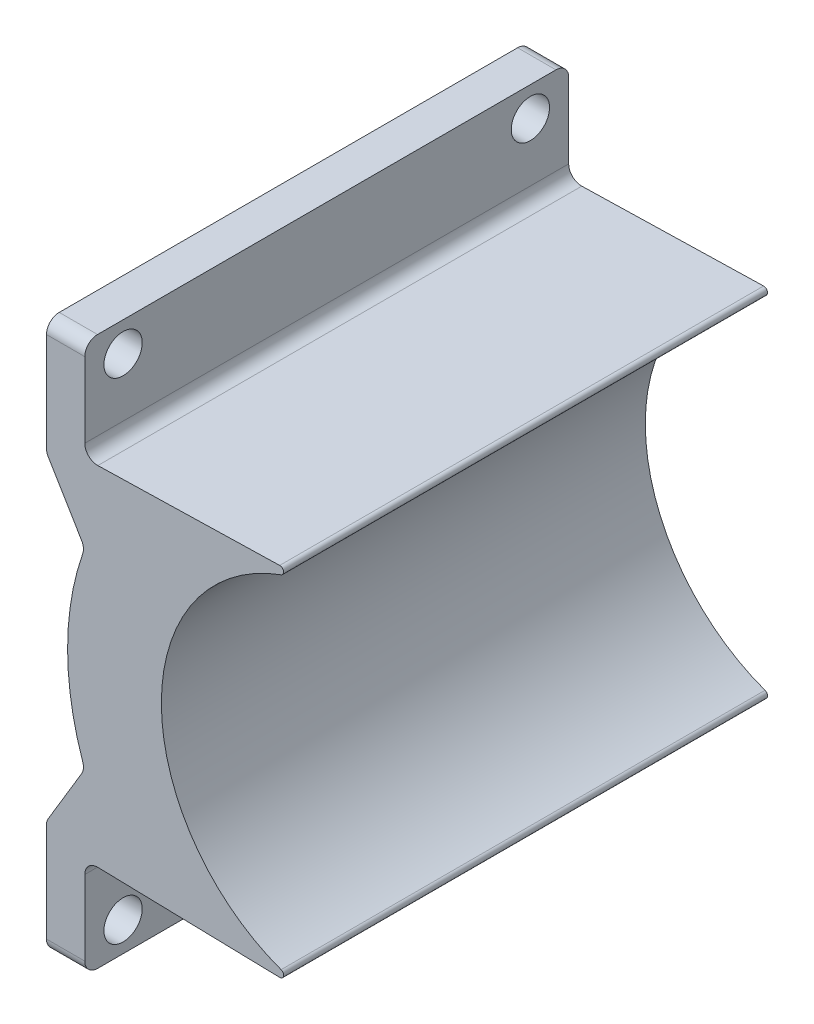
SolidWorks part; units mm, degrees
ref_plane "前视基准面" through (0, 0, 0) normal (0, 0, 1) x (1, 0, 0)
ref_plane "上视基准面" through (0, 0, 0) normal (0, 1, 0) x (1, 0, 0)
ref_plane "右视基准面" through (0, 0, 0) normal (1, 0, 0) x (0, 0, -1)
other "Configuration Table"
sketch "草图3" plane through (0, 0, 0) normal (0, 0, 1) x (1, 0, 0)
  line L0 (0, 0) -> (0, -7.2) construction
  line L1 (0, -7.2) -> (19.3716, -7.2636) construction
  line L2 (0, 0) -> (3, 0) construction
  line L3 (3, 0) -> (3, -5.5) construction
  line L4 (3, -5.5) -> (14.2314, -2.7878) construction
  line L5 (-1.5, 0) -> (-4.5, 0)
  line L6 (-4.5, 0) -> (-4.5, -9)
  line L7 (-1.5, 0) -> (-1.5, -7.9)
  line L8 (-1.5, -7.9) -> (16.2755, -7.4665)
  line L9 (-4.5, -9) -> (-1.5, -14)
  line L10 (-6.7339, -21.5) -> (12.0368, -21.5) construction
  line L11 (-4.5, -34) -> (-1.5, -29)
  line L12 (-1.5, -35.1) -> (16.2755, -35.5335)
  line L13 (-1.5, -43) -> (-1.5, -35.1)
  line L14 (-1.5, -43) -> (-4.5, -43)
  line L15 (-4.5, -43) -> (-4.5, -34)
  arc A0 (19.3716, -7.2636) -> (33, -21.5) centre (18.75, -21.5) cw construction
  arc A1 (14.2314, -2.7878) -> (38, -21.5) centre (18.75, -21.5) cw construction
  arc A2 (16.2755, -7.4665) -> (16.2755, -35.5335) centre (18.75, -21.5) ccw
  arc A3 (-1.5, -14) -> (-1.5, -29) centre (18.75, -21.5) ccw
  point P3 (12.0368, -25.9178)
  point P9 (35.0735, -25.6905)
  point P14 (-4.5536, -29.3279)
  point P21 (-1.7579, -9)
  point P22 (-4.5, -11.3653)
  point P23 (-1.8481, -15.7128)
  point P24 (-1.5, -9)
  point P25 (0, 0)
  point P26 (-1.5, -15.0914)
  point P27 (0, 0)
  point P34 (0, 0)
  point P35 (0, -7.2005)
  point P36 (0, -6.7458)
  point P37 (-13.5763, -9.2465)
  point P38 (-6.7562, -16.1113)
  point P39 (9.8393, -3.1843)
  point P40 (38, -26.2967)
  point P41 (18.1912, -8.702)
  point P42 (-4.5, -7.2)
  point P43 (-1.5, -11.141)
  point P44 (-4.5, -9.3981)
  point P45 (-1.5, -13.9448)
  point P46 (0, 0)
  point P47 (-1.5, -7.8403)
  dimension "D4" = 14.25
  dimension "D5" = 19.25
  dimension "D9" = 14.3
  dimension "D11" = 3
  dimension "D13" = 14.25
  dimension "D14" = 9
  dimension "D2" = 5.5
  dimension "D3" = 3
  dimension "D6" = 35
  dimension "D7" = 87.5
  dimension "D8" = 16
  dimension "D10" = 160
  dimension "D12" = 1.5
  dimension "D15" = 15
  dimension "D16" = 7.9
extrude "凸台-拉伸1" add sketch "草图3" along normal blind 37.9
sketch "草图4" plane through (-4.5, 0, 0) normal (-1, 0, 0) x (0, 0, 1)
  line L0 (37.9, -43) -> (0, -43) construction
  line L1 (0, -34) -> (0, -43) construction
  line L2 (18.95, -43) -> (18.95, -39.4204) construction
  line L3 (37.9, -21.5) -> (34.9, -21.5) construction
  line L4 (37.9, -29) -> (37.9, -14) construction
  circle A0 centre (3, -40.7) radius 1.5
  circle A1 centre (34.9, -40.7) radius 1.5
  circle A2 centre (3, -2.3) radius 1.5
  circle A3 centre (34.9, -2.3) radius 1.5
  dimension "D1" = 3
  dimension "D2" = 2.3
  dimension "D3" = 3
extrude "切除-拉伸1" cut sketch "草图4" against normal up to next
fillet "圆角1" radius 0.3 2 edges at (16.2755, -35.5335, 18.95) (16.2755, -7.4665, 18.95)
fillet "圆角2" radius 1 10 edges at (-1.5, -7.9, 18.95) (-1.5, -35.1, 18.95) (-3, -43, 0) (-3, -43, 37.9) (-4.5, -34, 18.95) (-1.5, -29, 18.95) (-1.5, -14, 18.95) (-4.5, -9, 18.95) (-3, 0, 0) (-3, 0, 37.9)
